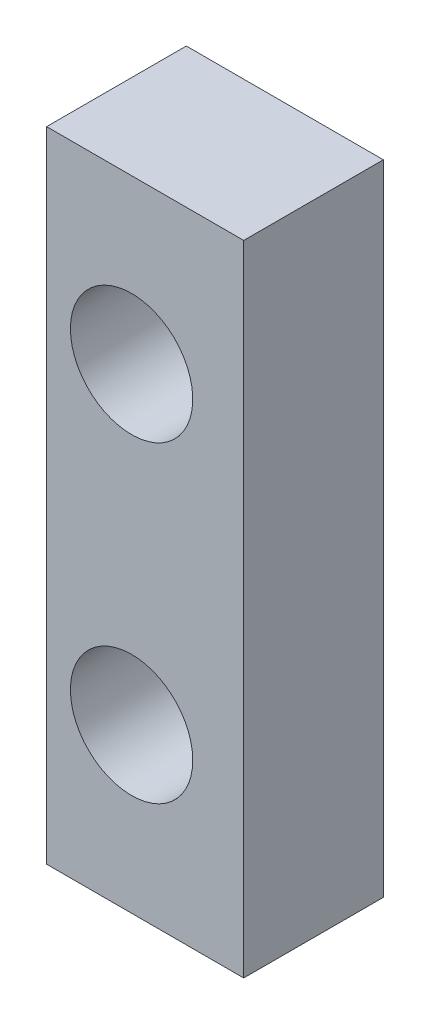
SolidWorks part; units mm, degrees
ref_plane "前视基准面" through (0, 0, 0) normal (0, 0, 1) x (1, 0, 0)
ref_plane "上视基准面" through (0, 0, 0) normal (0, 1, 0) x (1, 0, 0)
ref_plane "右视基准面" through (0, 0, 0) normal (1, 0, 0) x (0, 0, -1)
sketch "草图2" plane through (0, 0, 0) normal (0, 0, 1) x (1, 0, 0)
  line L0 (-80.4423, -13.4671) -> (-72.1701, -13.4671) construction
  line L1 (-77.6686, -8.8931) -> (-77.6686, -18.0411)
  line L2 (-77.6686, -18.0411) -> (-74.8464, -18.0411)
  line L3 (-74.8464, -18.0411) -> (-74.8464, -8.8931)
  line L4 (-77.6686, -8.8931) -> (-74.8464, -8.8931)
  circle A0 centre (-76.4521, -15.7055) radius 0.8759
  circle A1 centre (-76.4521, -11.2288) radius 0.8759
  point P7 (-74.8464, -13.4671)
  point P8 (-77.6686, -13.4671)
  point P10 (-76.4521, -15.7055)
extrude "凸台-拉伸1" add sketch "草图2" along normal blind 2
